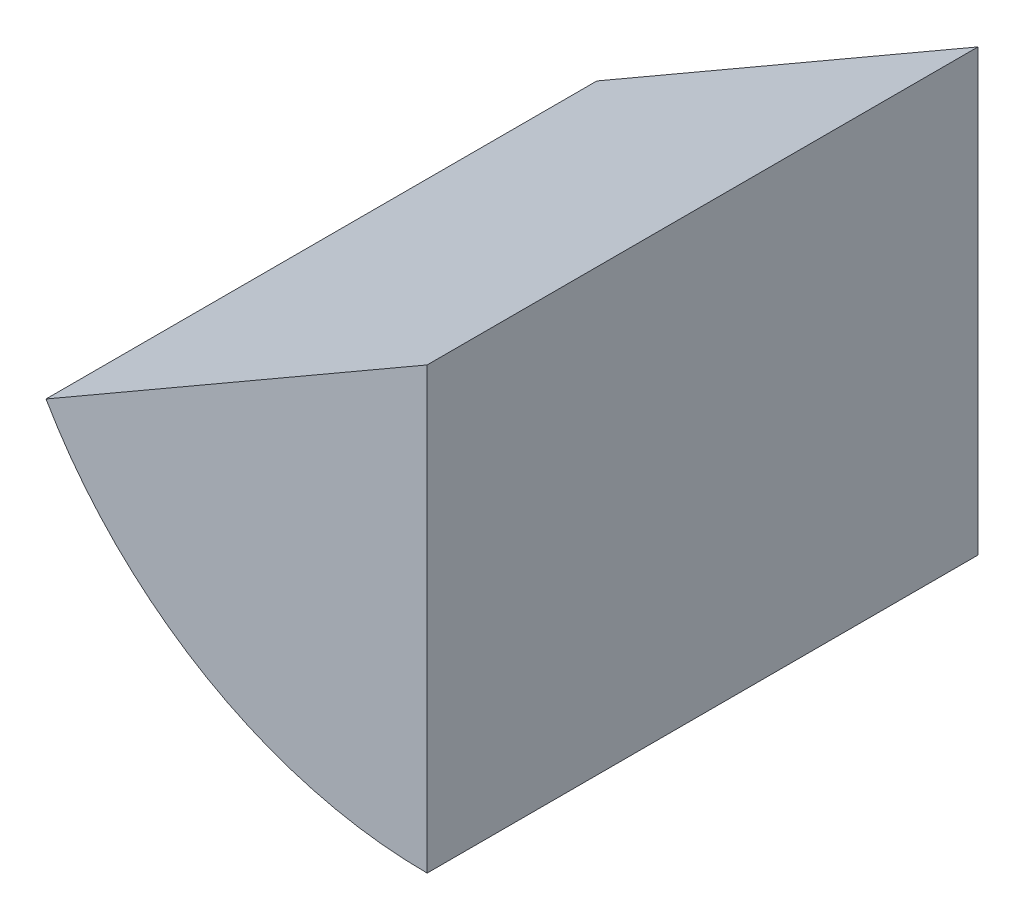
SolidWorks part; units mm, degrees
ref_plane "Alzado" through (0, 0, 0) normal (0, 0, 1) x (1, 0, 0)
ref_plane "Planta" through (0, 0, 0) normal (0, 1, 0) x (1, 0, 0)
ref_plane "Vista lateral" through (0, 0, 0) normal (1, 0, 0) x (0, 0, -1)
sketch "Croquis1" plane through (0, 0, 0) normal (0, 0, 1) x (1, 0, 0)
  line L0 (0, 0) -> (0, -39.9464)
  line L1 (0, 0) -> (-34.5946, -19.9732)
  arc A0 (-34.5946, -19.9732) -> (0, -39.9464) centre (0, 0) ccw
  dimension "D1" = 60
extrude "Saliente-Extruir1" add sketch "Croquis1" along normal blind 50
sketch "Croquis2" plane through (0, 0, 0) normal (0, 0, -1) x (-1, 0, 0)
  circle A0 centre (12.1915, -22.131) radius 5.0219
extrude "Cortar-Extruir1" cut sketch "Croquis2" against normal blind 10
